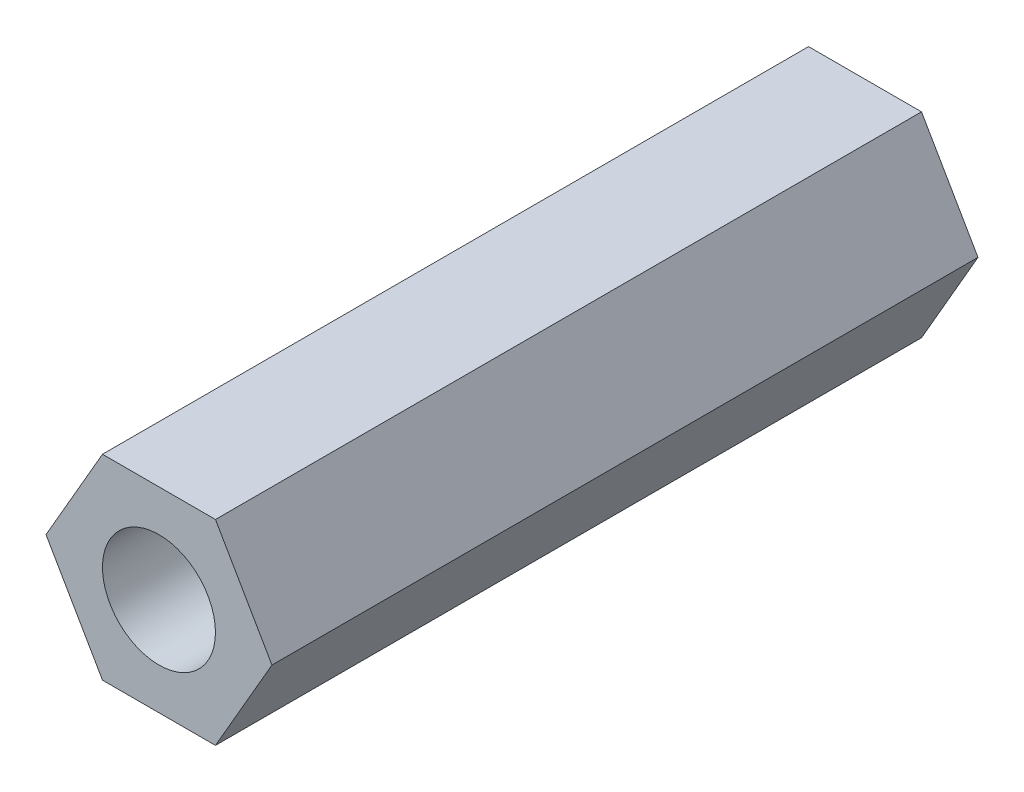
SolidWorks part; units mm, degrees
ref_plane "前视基准面" through (0, 0, 0) normal (0, 0, 1) x (1, 0, 0)
ref_plane "上视基准面" through (0, 0, 0) normal (0, 1, 0) x (1, 0, 0)
ref_plane "右视基准面" through (0, 0, 0) normal (1, 0, 0) x (0, 0, -1)
sketch "草图1" plane through (0, 0, 0) normal (0, 0, 1) x (1, 0, 0)
  line L1 (49.1306, 79.3672) -> (47.1306, 82.8313)
  line L2 (47.1306, 82.8313) -> (43.1306, 82.8313)
  line L3 (43.1306, 82.8313) -> (41.1306, 79.3672)
  line L4 (41.1306, 79.3672) -> (43.1306, 75.9031)
  line L5 (43.1306, 75.9031) -> (47.1306, 75.9031)
  line L6 (47.1306, 75.9031) -> (49.1306, 79.3672)
  circle A0 centre (45.1306, 79.3672) radius 3.4641 construction
  circle A1 centre (45.1306, 79.3672) radius 2
  point P9 (0, 0)
  point P10 (45.1306, 79.3672)
  dimension "D2" = 4
  dimension "D1" = 4
extrude "凸台-拉伸1" add sketch "草图1" along normal up to vertex (25 mm away)
